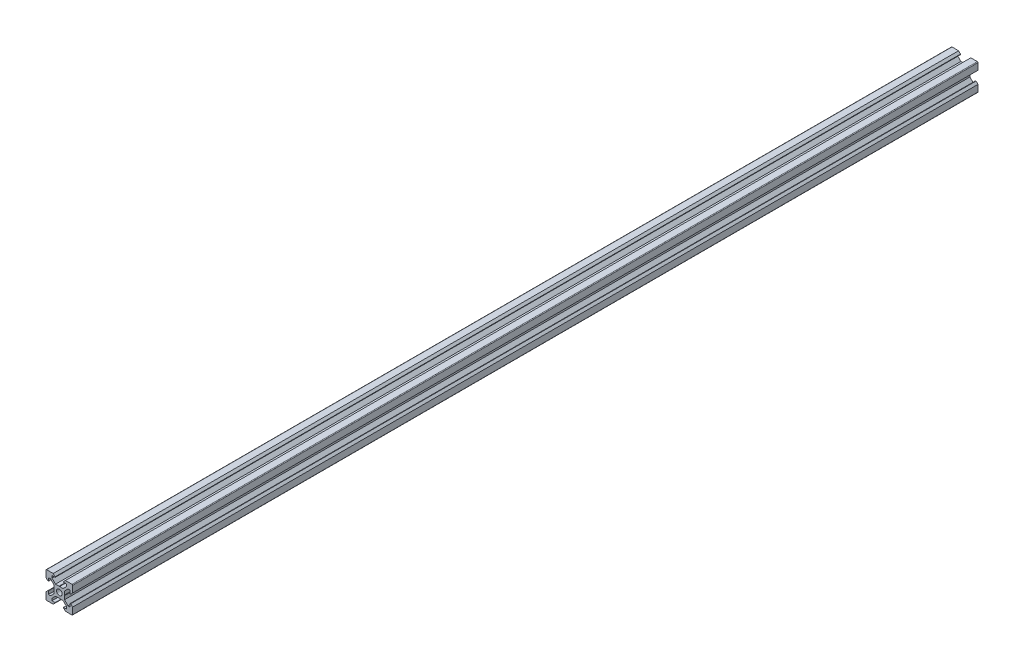
SolidWorks part; units mm, degrees
material "6061-T6 (SS)"
ref_plane "Front Plane" through (0, 0, 0) normal (0, 0, 1) x (1, 0, 0)
ref_plane "Top Plane" through (0, 0, 0) normal (0, 1, 0) x (1, 0, 0)
ref_plane "Right Plane" through (0, 0, 0) normal (1, 0, 0) x (0, 0, -1)
sketch "Sketch1" plane through (0, 0, 0) normal (0, 0, 1) x (1, 0, 0)
  line L1 (9.5, -10) -> (-9.5, -10)
  line L2 (10, -9.5) -> (10, 9.5)
  line L3 (9.5, 10) -> (-9.5, 10)
  line L4 (-10, -9.5) -> (-10, 9.5)
  line L5 (10, -10) -> (-10, 10) construction
  line L6 (10, 10) -> (-10, -10) construction
  circle A0 centre (0, 0) radius 2.1
  arc A1 (-9.5, 10) -> (-10, 9.5) centre (-9.5, 9.5) ccw
  arc A2 (10, 9.5) -> (9.5, 10) centre (9.5, 9.5) ccw
  arc A3 (9.5, -10) -> (10, -9.5) centre (9.5, -9.5) ccw
  arc A4 (-9.5, -10) -> (-10, -9.5) centre (-9.5, -9.5) cw
  point P0 (0, 0)
  line B0 (0, 0) -> (0, 10) construction
  line B1 (0, 3.69) -> (-0.21, 3.9)
  line B2 (-0.21, 3.9) -> (-2.8393, 3.9)
  line B3 (-2.8393, 3.9) -> (-5.5, 6.5607)
  line B4 (-5.5, 6.5607) -> (-5.5, 8.2)
  line B5 (-5.5, 8.2) -> (-3.125, 8.2)
  line B6 (-3.125, 8.2) -> (-3.125, 8.545)
  line B7 (-3.125, 8.545) -> (-4.58, 10)
  line B8 (-4.58, 10) -> (4.58, 10)
  line B9 (0, 0) -> (-5.9132, 5.9132) construction
  line B10 (3.125, 8.545) -> (4.58, 10)
  line B11 (3.125, 8.2) -> (3.125, 8.545)
  line B12 (5.5, 8.2) -> (3.125, 8.2)
  line B13 (5.5, 6.5607) -> (5.5, 8.2)
  line B14 (2.8393, 3.9) -> (5.5, 6.5607)
  line B15 (0.21, 3.9) -> (2.8393, 3.9)
  line B16 (0, 3.69) -> (0.21, 3.9)
  line B17 (0, 0) -> (-10, 0) construction
  line B18 (-3.69, 0) -> (-3.9, -0.21)
  line B19 (-3.9, -0.21) -> (-3.9, -2.8393)
  line B20 (-3.9, -2.8393) -> (-6.5607, -5.5)
  line B21 (-6.5607, -5.5) -> (-8.2, -5.5)
  line B22 (-8.2, -5.5) -> (-8.2, -3.125)
  line B23 (-8.2, -3.125) -> (-8.545, -3.125)
  line B24 (-8.545, -3.125) -> (-10, -4.58)
  line B25 (-10, -4.58) -> (-10, 4.58)
  line B26 (0, 0) -> (-5.9132, -5.9132) construction
  line B27 (-8.545, 3.125) -> (-10, 4.58)
  line B28 (-8.2, 3.125) -> (-8.545, 3.125)
  line B29 (-8.2, 5.5) -> (-8.2, 3.125)
  line B30 (-6.5607, 5.5) -> (-8.2, 5.5)
  line B31 (-3.9, 2.8393) -> (-6.5607, 5.5)
  line B32 (-3.9, 0.21) -> (-3.9, 2.8393)
  line B33 (-3.69, 0) -> (-3.9, 0.21)
  line B34 (0, 0) -> (0, -10) construction
  line B35 (0, -3.69) -> (0.21, -3.9)
  line B36 (0.21, -3.9) -> (2.8393, -3.9)
  line B37 (2.8393, -3.9) -> (5.5, -6.5607)
  line B38 (5.5, -6.5607) -> (5.5, -8.2)
  line B39 (5.5, -8.2) -> (3.125, -8.2)
  line B40 (3.125, -8.2) -> (3.125, -8.545)
  line B41 (3.125, -8.545) -> (4.58, -10)
  line B42 (4.58, -10) -> (-4.58, -10)
  line B43 (0, 0) -> (5.9132, -5.9132) construction
  line B44 (-3.125, -8.545) -> (-4.58, -10)
  line B45 (-3.125, -8.2) -> (-3.125, -8.545)
  line B46 (-5.5, -8.2) -> (-3.125, -8.2)
  line B47 (-5.5, -6.5607) -> (-5.5, -8.2)
  line B48 (-2.8393, -3.9) -> (-5.5, -6.5607)
  line B49 (-0.21, -3.9) -> (-2.8393, -3.9)
  line B50 (0, -3.69) -> (-0.21, -3.9)
  line B51 (0, 0) -> (10, 0) construction
  line B52 (3.69, 0) -> (3.9, 0.21)
  line B53 (3.9, 0.21) -> (3.9, 2.8393)
  line B54 (3.9, 2.8393) -> (6.5607, 5.5)
  line B55 (6.5607, 5.5) -> (8.2, 5.5)
  line B56 (8.2, 5.5) -> (8.2, 3.125)
  line B57 (8.2, 3.125) -> (8.545, 3.125)
  line B58 (8.545, 3.125) -> (10, 4.58)
  line B59 (10, 4.58) -> (10, -4.58)
  line B60 (0, 0) -> (5.9132, 5.9132) construction
  line B61 (8.545, -3.125) -> (10, -4.58)
  line B62 (8.2, -3.125) -> (8.545, -3.125)
  line B63 (8.2, -5.5) -> (8.2, -3.125)
  line B64 (6.5607, -5.5) -> (8.2, -5.5)
  line B65 (3.9, -2.8393) -> (6.5607, -5.5)
  line B66 (3.9, -0.21) -> (3.9, -2.8393)
  line B67 (3.69, 0) -> (3.9, -0.21)
  dimension "D1" = 4.2
  dimension "D3" = 0.5
  dimension "D2" = 20
sketch_block_instance "V Slot 1-4"
sketch_block "V Slot 1" parameters "D1"=10, "D2"=11, "D3"=4.3, "D4"=1.8, "D5"=0.21, "D6"=45, "D7"=9.16, "D8"=1.5, "D9"=6.25
sketch_block_instance "V Slot 1-5"
sketch_block_instance "V Slot 1-6"
sketch_block_instance "V Slot 1-7"
extrude "Boss-Extrude1" add sketch "Sketch1" along normal blind 680 contours B67 B52 B53 B54 B55 B56 B57 B58 L2 A2 L3 B10 B11 B12 B13 B14 B15 B16 B1 B2 B3 B4 B5 B6 B7 A1 L4 B27 B28 B29 B30 B31 B32 B33 B18 B19 B20 B21 B22 B23 B24 A4 L1 B44 B45 B46 B47 B48 B49
